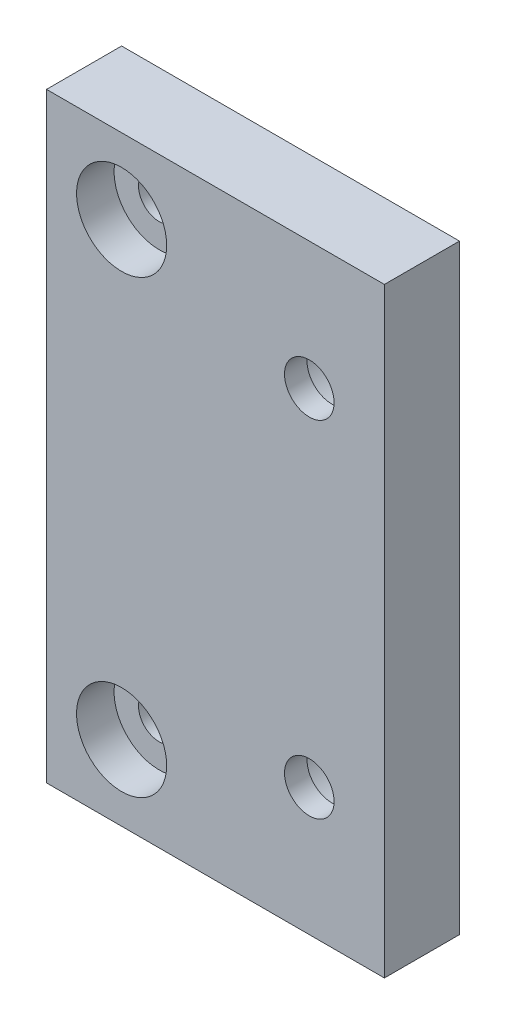
SolidWorks part; units mm, degrees
ref_plane "Plan de face" through (0, 0, 0) normal (0, 0, 1) x (1, 0, 0)
ref_plane "Plan de dessus" through (0, 0, 0) normal (0, 1, 0) x (1, 0, 0)
ref_plane "Plan de droite" through (0, 0, 0) normal (1, 0, 0) x (0, 0, -1)
sketch "Esquisse1" plane through (0, 0, 0) normal (0, 0, 1) x (1, 0, 0)
  line L0 (-1.1781, 24.138) -> (-1.1781, -21.862) construction
  line L1 (-36.1781, 41.138) -> (8.8219, 41.138)
  line L2 (-36.1781, 41.138) -> (-36.1781, -38.862)
  line L3 (-36.1781, -38.862) -> (8.8219, -38.862)
  line L4 (8.8219, 41.138) -> (8.8219, -38.862)
  circle A0 centre (-1.1781, 24.138) radius 3.3
  circle A3 centre (-1.1781, -21.862) radius 3.3
  circle A4 centre (-26.1781, 31.138) radius 2.75
  circle A7 centre (-26.1781, -28.862) radius 2.75
  point P12 (-1.1781, 1.138)
  point P13 (8.8219, 1.138)
  dimension "D1" = 6.6
  dimension "D7" = 5.5
  dimension "D3" = 6.6
  dimension "D2" = 10
  dimension "D4" = 46
  dimension "D5" = 80
  dimension "D6" = 45
  dimension "D8" = 10
  dimension "D9" = 10
  dimension "D11" = 10
extrude "Boss.-Extru.1" add sketch "Esquisse1" along normal blind 10
sketch "Esquisse2" plane through (0, 0, 10) normal (0, 0, 1) x (1, 0, 0)
  circle A4 centre (-26.1781, 31.138) radius 6
  circle A5 centre (-26.1781, -28.862) radius 6
  dimension "D1" = 12
extrude "Enlèv. mat.-Extru.1" cut sketch "Esquisse2" against normal blind 5
sketch "Esquisse3" plane through (0, 0, 0) normal (0, 0, -1) x (-1, 0, 0)
  circle A8 centre (1.1781, 24.138) radius 7
  circle A9 centre (1.1781, -21.862) radius 7
  dimension "D1" = 14
extrude "Enlèv. mat.-Extru.3" cut sketch "Esquisse3" against normal blind 7
